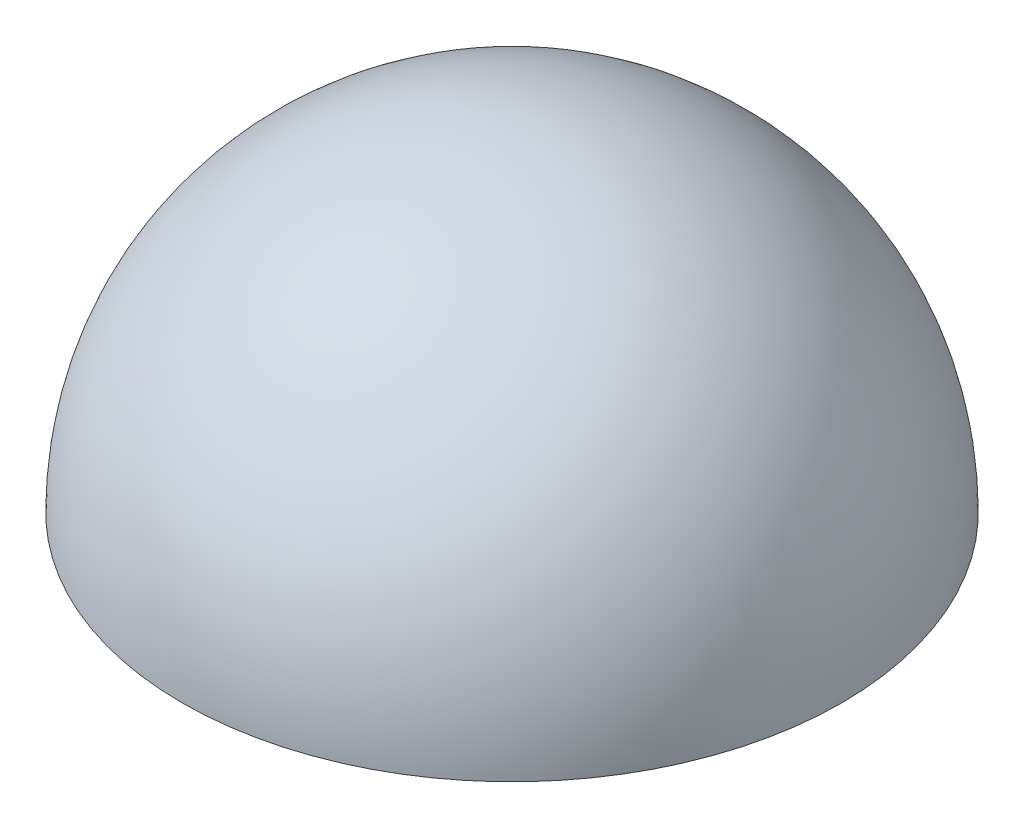
SolidWorks part; units mm, degrees
ref_plane "Front Plane" through (0, 0, 0) normal (0, 0, 1) x (1, 0, 0)
ref_plane "Top Plane" through (0, 0, 0) normal (0, 1, 0) x (1, 0, 0)
ref_plane "Right Plane" through (0, 0, 0) normal (1, 0, 0) x (0, 0, -1)
sketch "Sketch1" plane through (0, 0, 0) normal (0, 0, 1) x (1, 0, 0)
  line L0 (-25, 0) -> (0, 0)
  line L1 (0, 0) -> (0, 25) construction
  line L2 (0, 0) -> (0, 25)
  arc A0 (-25, 0) -> (0, 25) centre (0, 0) cw
  dimension "D1" = 25
revolve "Revolve1" add sketch "Sketch1" angle 360 about L1
shell "Shell1" thickness 5
